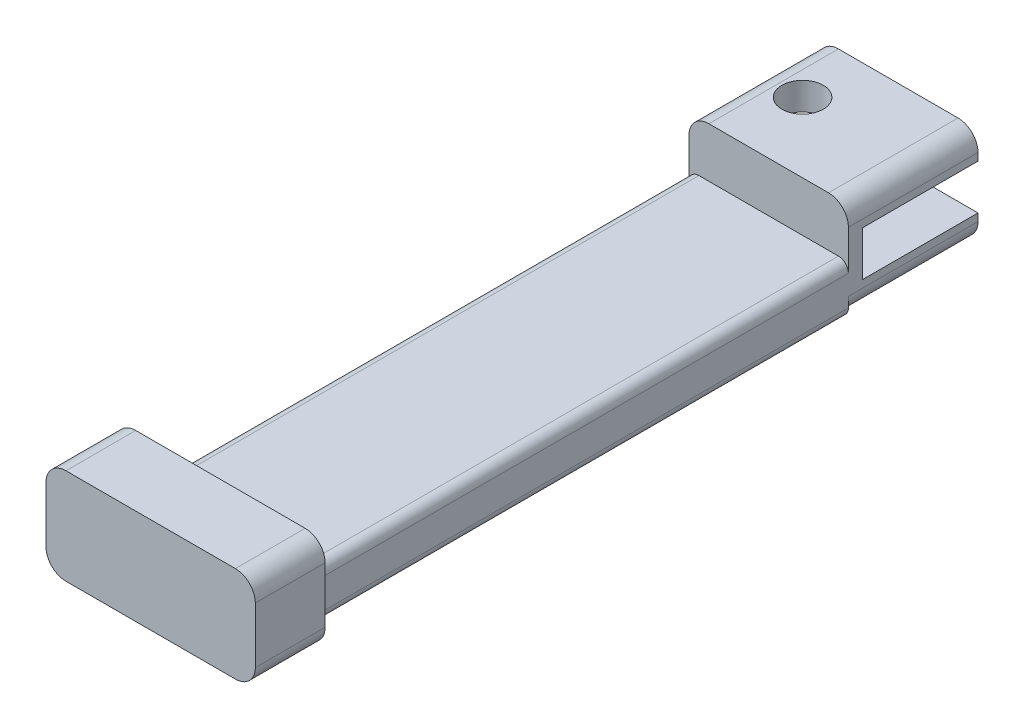
SolidWorks part; units mm, degrees
ref_plane "Front Plane" through (0, 0, 0) normal (0, 0, 1) x (1, 0, 0)
ref_plane "Top Plane" through (0, 0, 0) normal (0, 1, 0) x (1, 0, 0)
ref_plane "Right Plane" through (0, 0, 0) normal (1, 0, 0) x (0, 0, -1)
sketch "S01 - TPU 16 by 5 gauge" plane through (0, 0, 0) normal (0, 0, 1) x (1, 0, 0)
  line L0 (-7, -5) -> (7, -5)
  line L1 (8, -4) -> (8, -1)
  line L2 (7, 0) -> (-7, 0)
  line L3 (-8, -1) -> (-8, -4)
  arc A0 (7, -5) -> (8, -4) centre (7, -4) ccw
  arc A1 (8, -1) -> (7, 0) centre (7, -1) ccw
  arc A2 (-7, 0) -> (-8, -1) centre (-7, -1) ccw
  arc A3 (-8, -4) -> (-7, -5) centre (-7, -4) ccw
  dimension "D1" = 1
  dimension "D2" = 8
  dimension "D3" = 8
  dimension "D4" = 5
extrude "01 - TPU 16 by 5 gauge" add sketch "S01 - TPU 16 by 5 gauge" along normal blind 55 from offset 13
sketch "S02 - Cord end block" plane through (0, 0, 0) normal (0, 0, 1) x (1, 0, 0)
  line L0 (-6, -5) -> (6, -5)
  line L1 (8, -3) -> (8, 3)
  line L2 (6, 5) -> (-6, 5)
  line L3 (-8, 3) -> (-8, -3)
  arc A0 (6, -5) -> (8, -3) centre (6, -3) ccw
  arc A1 (8, 3) -> (6, 5) centre (6, 3) ccw
  arc A2 (-6, 5) -> (-8, 3) centre (-6, 3) ccw
  arc A3 (-8, -3) -> (-6, -5) centre (-6, -3) ccw
  dimension "D1" = 2
  dimension "D2" = 8
  dimension "D3" = 8
  dimension "D4" = 5
  dimension "D5" = 5
extrude "02 - Cord end block" add sketch "S02 - Cord end block" along normal blind 13
sketch "S03 - Captured tail button" plane through (0, 0, 0) normal (0, 0, 1) x (1, 0, 0)
  line L0 (-8.5, -5) -> (8.5, -5)
  line L1 (10.5, -3) -> (10.5, 2.6)
  line L2 (8.5, 4.6) -> (-8.5, 4.6)
  line L3 (-10.5, 2.6) -> (-10.5, -3)
  arc A0 (8.5, -5) -> (10.5, -3) centre (8.5, -3) ccw
  arc A1 (10.5, 2.6) -> (8.5, 4.6) centre (8.5, 2.6) ccw
  arc A2 (-8.5, 4.6) -> (-10.5, 2.6) centre (-8.5, 2.6) ccw
  arc A3 (-10.5, -3) -> (-8.5, -5) centre (-8.5, -3) ccw
  dimension "D1" = 2
  dimension "D2" = 10.5
  dimension "D3" = 10.5
  dimension "D4" = 4.6
  dimension "D5" = 5
extrude "03 - Captured tail button" add sketch "S03 - Captured tail button" along normal blind 7 from offset 68
sketch "S04 - Open two-ear pin clevis" plane through (0, 0, 0) normal (0, 0, 1) x (1, 0, 0)
  line L0 (-9, -2.25) -> (9, -2.25)
  line L1 (9, -2.25) -> (9, 2.25)
  line L2 (9, 2.25) -> (-9, 2.25)
  line L3 (-9, 2.25) -> (-9, -2.25)
  dimension "D1" = 9
  dimension "D2" = 9
  dimension "D3" = 2.25
  dimension "D4" = 2.25
extrude "04 - Open two-ear pin clevis" cut sketch "S04 - Open two-ear pin clevis" along normal blind 11.8 from offset 0.2 offset against normal yes
sketch3d "Plane points - Shoulder pin through both ears"
  point P0 (0, 0, 0)
  point P1 (18, 0, 0)
  point P2 (0, 0, -18)
ref_plane "Drilling plane - Shoulder pin through both ears" through (0, 0, 0) normal (0, 1, 0) x (1, 0, 0)
sketch "S05 - Shoulder pin through both ears" plane through (0, 0, 0) normal (0, 1, 0) x (1, 0, 0)
  circle A0 centre (-3.6, -6) radius 2.08
  dimension "D1" = 4.16
  dimension "D2" = 3.6
  dimension "D3" = 6
extrude "05 - Shoulder pin through both ears" cut sketch "S05 - Shoulder pin through both ears" along normal blind 10.4 from offset 5.2
